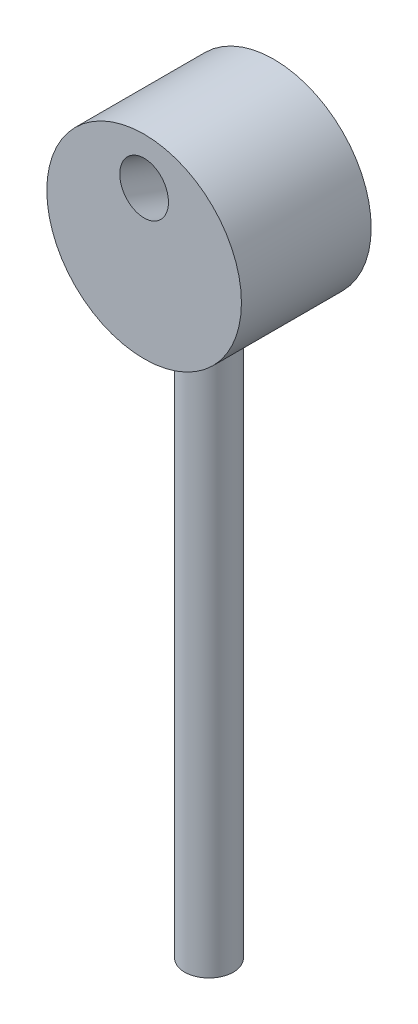
SolidWorks part; units mm, degrees
ref_plane "Front Plane" through (0, 0, 0) normal (0, 0, 1) x (1, 0, 0)
ref_plane "Top Plane" through (0, 0, 0) normal (0, 1, 0) x (1, 0, 0)
ref_plane "Right Plane" through (0, 0, 0) normal (1, 0, 0) x (0, 0, -1)
sketch "Sketch1" plane through (0, 0, 0) normal (0, 0, 1) x (1, 0, 0)
  circle A0 centre (0, 0) radius 1.5
  dimension "D1" = 3
extrude "Boss-Extrude1" add sketch "Sketch1" along normal mid plane 2
sketch "Sketch4" plane through (0, 0, 1) normal (0, 0, 1) x (1, 0, 0)
  circle A0 centre (0, 0.78) radius 0.38
  circle A1 centre (0, 0) radius 1.5 construction
  point P2 (0, 1.5)
  point P3 (0, 1.16)
  dimension "D1" = 0.76
  dimension "D2" = 0.34
sketch "Sketch5" plane through (0, 0, 0) normal (1, 0, 0) x (0, 0, -1)
  line L0 (-1, 1.16) -> (2.5177, -0.1203)
  line L1 (-1, 1.5) -> (0.8469, 1.5) construction
  line L2 (-1, 0.4) -> (1.4613, -0.4958)
  line L3 (-1, 1.16) -> (-1, 0.4) construction
  line L4 (-1, 0.78) -> (-0.3495, 0.5432)
  point P12 (0, 0)
  point P13 (0, 0)
  dimension "D1" = 20
ref_plane "Plane1" through (0, -10, 0) normal (0, 1, 0) x (1, 0, 0)
sketch "Sketch6" plane through (0, -10, 0) normal (0, 1, 0) x (1, 0, 0)
  circle A0 centre (0, 0) radius 0.375
  point P4 (0, 0)
  dimension "D1" = 0.75
extrude "Boss-Extrude2" add sketch "Sketch6" along normal up to next contours A0
ref_plane "Plane2" through (0, 0.78, 1) normal (0, -0.342, -0.9397) x (-1, 0, 0)
sketch "Sketch7" plane through (0, 0.78, 1) normal (0, -0.342, -0.9397) x (-1, 0, 0)
  circle A0 centre (0, 0) radius 0.375
  dimension "D1" = 0.75
extrude "Cut-Extrude1" cut sketch "Sketch7" against normal mid plane 10 contours A0
